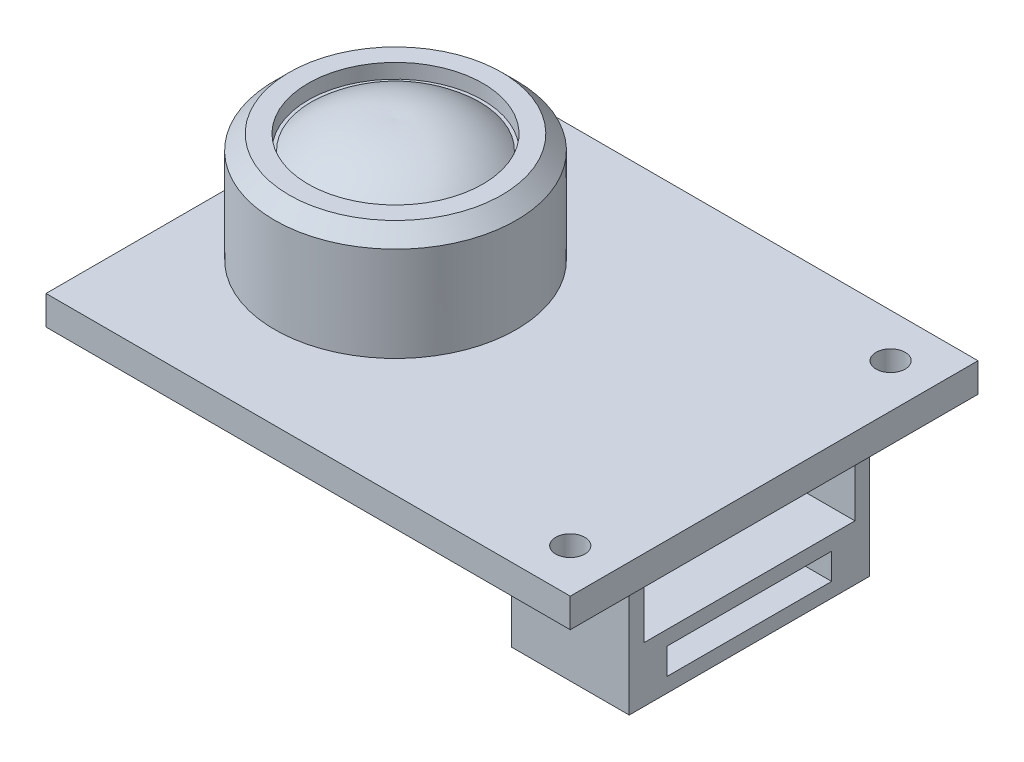
SolidWorks part; units mm, degrees
ref_plane "Front Plane" through (0, 0, 0) normal (0, 0, 1) x (1, 0, 0)
ref_plane "Top Plane" through (0, 0, 0) normal (0, 1, 0) x (1, 0, 0)
ref_plane "Right Plane" through (0, 0, 0) normal (1, 0, 0) x (0, 0, -1)
sketch "Sketch1" plane through (0, 0, 0) normal (0, 1, 0) x (1, 0, 0)
  line L1 (0, 0) -> (18, 0)
  line L2 (0, 0) -> (0, 14)
  line L3 (0, 14) -> (18, 14)
  line L4 (18, 0) -> (18, 14)
  circle A0 centre (16.5, 12.5) radius 0.5
  circle A1 centre (16.5, 1.5) radius 0.5
  dimension "D3" = 16.5
  dimension "D4" = 16.5
  dimension "D5" = 1
  dimension "D6" = 1
  dimension "D7" = 1.5
  dimension "D8" = 1.5
  dimension "D1" = 18
  dimension "D2" = 14
extrude "Boss-Extrude1" add sketch "Sketch1" along normal blind 1
sketch "Sketch2" plane through (0, 1, 0) normal (0, 1, 0) x (1, 0, 0)
  line L0 (0, 14) -> (0, 0) construction
  line L1 (18, 14) -> (0, 14) construction
  circle A0 centre (5, 7) radius 4.15
  dimension "D1" = 8.3
  dimension "D2" = 5
  dimension "D3" = 7
extrude "Boss-Extrude2" add sketch "Sketch2" along normal blind 3.75
sketch "Sketch3" plane through (0, 0, 0) normal (0, -1, 0) x (-1, 0, 0)
  line L0 (0, 0) -> (-18, 0) construction
  line L1 (-17.15, 11.125) -> (-13.1, 11.125)
  line L2 (-17.15, 11.125) -> (-17.15, 2.875)
  line L3 (-17.15, 2.875) -> (-13.1, 2.875)
  line L4 (-13.1, 11.125) -> (-13.1, 2.875)
  line L5 (-18, 0) -> (-18, 14) construction
  dimension "D1" = 8.25
  dimension "D2" = 2.875
  dimension "D3" = 4.05
  dimension "D4" = 0.85
extrude "Boss-Extrude3" add sketch "Sketch3" along normal blind 4.4
sketch "Sketch4" plane through (17.15, 0, 0) normal (1, 0, 0) x (0, 0, -1)
  line L0 (2.875, -4.4) -> (2.875, 0) construction
  line L1 (3.375, -0.5) -> (10.625, -0.5)
  line L2 (3.375, -0.5) -> (3.375, -2.5)
  line L3 (3.375, -2.5) -> (10.625, -2.5)
  line L4 (10.625, -0.5) -> (10.625, -2.5)
  line L5 (4.175, -3) -> (9.825, -3)
  line L6 (4.175, -3) -> (4.175, -3.9)
  line L7 (4.175, -3.9) -> (9.825, -3.9)
  line L8 (9.825, -3) -> (9.825, -3.9)
  line L9 (11.125, -4.4) -> (11.125, 0) construction
  line L10 (11.125, -4.4) -> (2.875, -4.4) construction
  line L11 (11.125, 0) -> (2.875, 0) construction
  dimension "D1" = 2
  dimension "D2" = 0.5
  dimension "D3" = 0.5
  dimension "D4" = 1.3
  dimension "D5" = 1.3
  dimension "D6" = 0.5
  dimension "D7" = 0.5
  dimension "D8" = 0.5
extrude "Cut-Extrude1" cut sketch "Sketch4" against normal blind 3
sketch "Sketch5" plane through (0, 4.75, 0) normal (0, 1, 0) x (1, 0, 0)
  circle A0 centre (5, 7) radius 3
  circle A1 centre (5, 7) radius 4.15 construction
  dimension "D1" = 0
  dimension "D2" = 6
extrude "Cut-Extrude2" cut sketch "Sketch5" against normal blind 0.5
chamfer "Chamfer1" distance 0.5 angle 45 1 edges at (5, 4.75, -2.85)
ref_plane "Plane1" through (0, 0, -7) normal (0, 0, 1) x (1, 0, 0)
ref_plane "Plane2" through (5, 0, 0) normal (1, 0, 0) x (0, 0, -1)
sketch "Sketch7" plane through (0, 0, -7) normal (0, 0, 1) x (1, 0, 0)
  line L0 (4.9985, 4.2328) -> (4.9985, 5.2096)
  line L1 (4.9985, 5.2096) -> (4.9985, 4.2328)
  line L2 (4.9985, 4.2328) -> (2.0903, 4.2328)
  spline S0 degree 2 poles (2.0903, 4.2328) (3.3508, 5.3248) (4.9985, 5.2096) knots 0 0 0 1 1 1
revolve "Revolve2" add sketch "Sketch7" angle 360 about L0
